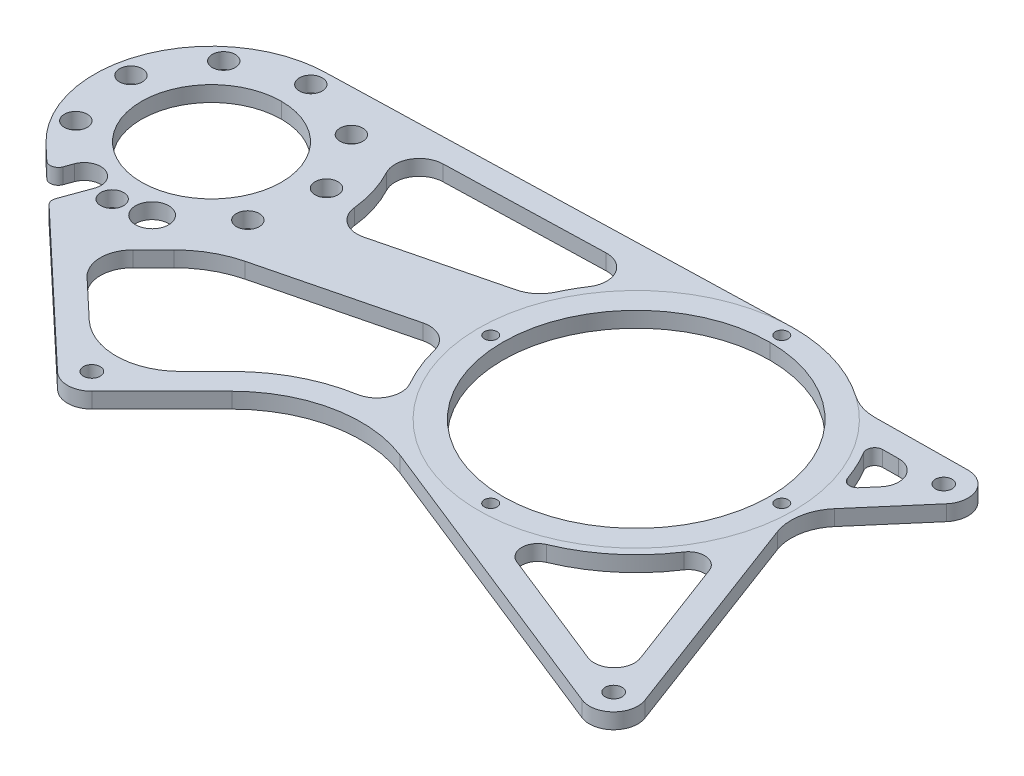
SolidWorks part; units mm, degrees
material "6061-T6 (SS)"
ref_plane "X-Y Datum" through (0, 0, 0) normal (0, 0, 1) x (1, 0, 0)
ref_plane "X-Z Datum" through (0, 0, 0) normal (0, 1, 0) x (1, 0, 0)
ref_plane "Y-Z Datum" through (0, 0, 0) normal (1, 0, 0) x (0, 0, -1)
sketch "Master Sketch " plane through (0, 0, 0) normal (0, 1, 0) x (1, 0, 0)
  line L0 (0, 0) -> (116.84, 0) construction
  line L1 (0, 0) -> (-54.61, 0) construction
  line L2 (116.84, 0) -> (228.6, 0) construction
  line L3 (228.6, 0) -> (228.6, 165.1) construction
  line L4 (123.19, 0) -> (123.19, 116.0018) construction
  line L5 (-54.61, 0) -> (-414.02, 0) construction
  line L6 (-54.61, 0) -> (-54.61, 127) construction
  line L7 (123.19, 168.4528) -> (123.19, 177.9778) construction
  line L8 (123.19, 116.0018) -> (228.6, 165.1) construction
  line L9 (123.19, 116.0018) -> (228.6, 0) construction
  line L10 (0, 0) -> (123.19, 116.0018) construction
  line L11 (0, 0) -> (-54.61, 127) construction
  line L12 (-54.61, 127) -> (123.19, 116.0018) construction
  line L13 (-54.61, 127) -> (228.6, 165.1) construction
  line L14 (0, 0) -> (0, 123.622) construction
  line L15 (-86.1521, 93.553) -> (-6.535, 18.4704)
  line L16 (-54.61, 172.974) -> (123.19, 177.9778)
  line L17 (192.5164, 124.5578) -> (212.8001, 148.1685)
  line L18 (169.599, 163.5141) -> (205.4727, 163.8999)
  line L19 (189.1339, 105.4429) -> (220.4344, 22.1488)
  line L20 (6.7352, 18.6648) -> (34.256, 46.1856)
  line L21 (207.987, 9.9519) -> (89.0101, 57.4446)
  circle A0 centre (0, 0) radius 12.7 construction
  circle A1 centre (228.6, 165.1) radius 12.7 construction
  circle A2 centre (228.6, 0) radius 12.7 construction
  circle A3 centre (-414.02, 0) radius 12.7 construction
  circle A4 centre (123.19, 116.0018) radius 52.451
  circle A5 centre (123.19, 116.0018) radius 57.15 construction
  circle A6 centre (123.19, 116.0018) radius 61.976 construction
  circle A7 centre (-54.61, 127) radius 45.974
  circle A8 centre (-54.61, 127) radius 39 construction
  circle A9 centre (205.5752, 154.3754) radius 3 construction
  circle A10 centre (211.5182, 18.7982) radius 3 construction
  circle A11 centre (0, 25.4) radius 3 construction
  circle A12 centre (0, 25.4) radius 9.525
  circle A13 centre (211.5182, 18.7982) radius 9.525
  circle A14 centre (205.5752, 154.3754) radius 9.525
  circle A15 centre (-67.9488, 90.352) radius 6.5
  circle A16 centre (-41.2712, 90.352) radius 6.5
  arc A17 (56.2619, 120.1418) -> (168.2859, 66.3745) centre (123.19, 116.0018) ccw construction
  arc A18 (123.19, 177.9778) -> (158.5311, 166.9138) centre (123.19, 116.0018) cw
  circle A19 centre (123.19, 116.0018) radius 67.056 construction
  arc A20 (192.5164, 124.5578) -> (189.1339, 105.4429) centre (206.9663, 112.1441) ccw
  arc A21 (169.599, 163.5141) -> (158.5311, 166.9138) centre (169.3942, 182.563) cw
  arc A22 (89.0101, 57.4446) -> (34.256, 46.1856) centre (70.177, 10.2646) ccw
  circle A23 centre (-54.61, 127) radius 25.908 construction
  circle A24 centre (-54.61, 127) radius 27.4955
  circle A25 centre (123.19, 173.1518) radius 2.5 construction
  point P9 (123.19, 0)
  point P23 (-54.61, 166)
  point P27 (-41.2712, 163.648)
  point P28 (-29.5413, 156.8757)
  point P29 (-20.835, 146.5)
  point P30 (-16.2025, 133.7723)
  point P31 (-16.2025, 120.2277)
  point P32 (-20.835, 107.5)
  point P33 (-29.5413, 97.1243)
  point P34 (-41.2712, 90.352)
  point P35 (-54.61, 88)
  point P36 (-67.9488, 90.352)
  point P37 (-79.6787, 97.1243)
  point P38 (-88.385, 107.5)
  point P39 (-93.0175, 120.2277)
  point P40 (-93.0175, 133.7723)
  point P41 (-88.385, 146.5)
  point P42 (-79.6787, 156.8757)
  point P43 (-67.9488, 163.648)
  point P44 (-54.61, 127)
  point P66 (190.246, 116.0018)
  point P74 (185.166, 116.0018)
  point P77 (163.0683, 163.4438)
  point P80 (74.3713, 70.0317)
  dimension "D1" = 105.41
  dimension "D2" = 25.4
  dimension "D8" = 116.0018
  dimension "D11" = 104.902
  dimension "D12" = 114.3
  dimension "D13" = 123.952
  dimension "D14" = 91.948
  dimension "D15" = 78
  dimension "D17" = 6
  dimension "D21" = 19.05
  dimension "D23" = 13
  dimension "D25" = 19.05
  dimension "D26" = 19.05
  dimension "D27" = 50.8
  dimension "D28" = 1.5875
  dimension "D30" = 51.816
  dimension "D31" = 5
  dimension "D3" = 165.1
  dimension "D4" = 171.45
  dimension "D5" = 111.76
  dimension "D6" = 116.84
  dimension "D7" = 54.61
  dimension "D9" = 642.62
  dimension "D10" = 127
  dimension "D18" = 25.4
  dimension "D19" = 25.4
  dimension "D20" = 25.4
  dimension "D22" = 228.6
  dimension "D29" = 45
  dimension "D24" = 5.08
  dimension "D16" = 18
extrude "Boss-Extrude2" add sketch "Master Sketch " along normal mid plane 6.096
hole_wizard "Ø5.0mm Dowel Hole1" positions "Sketch26" profile "Sketch27" hole size "Ø5.0" standard "ANSI Metric" end condition through all
sketch "Sketch26" plane through (0, 3.048, 0) normal (0, 1, 0) x (1, 0, 0)
  point P5 (123.19, 173.1518)
sketch "Sketch27" plane through (123.19, 3.048, -173.1518) normal (1, 0, 0) x (0, 0, 1)
  line L0 (0, 0) -> (0, 6.096)
  line L1 (0, 6.096) -> (2.5, 6.096)
  line L2 (2.5, 6.096) -> (2.5, 0)
  line L5 (2.5, 0) -> (0, 0)
  line L11 (0, -6.35) -> (0, 107.95) construction
  dimension "Thru Hole Dia." = 5
  dimension "Thru Hole Depth" = 6.096
pattern_circular "CirPattern4" count 4 over 360 about axis through (123.19, 0, -116.0018) along (0, 1, 0) of "Ø5.0mm Dowel Hole1"
hole_wizard "M6 Clearance Hole4" positions "Sketch20" profile "Sketch21" hole size "M6" standard "ANSI Metric" end condition through all
sketch "Sketch20" plane through (0, 3.048, 0) normal (0, 1, 0) x (1, 0, 0)
  point P0 (205.5752, 154.3754)
  point P3 (211.5182, 18.7982)
  point P6 (0, 25.4)
  point P9 (205.5752, 154.3754)
sketch "Sketch21" plane through (205.5752, 3.048, -154.3754) normal (1, 0, 0) x (0, 0, 1)
  line L0 (0, 0) -> (0, 6.096)
  line L1 (0, 6.096) -> (3.3, 6.096)
  line L2 (3.3, 6.096) -> (3.3, 0)
  line L5 (3.3, 0) -> (0, 0)
  line L11 (0, -6.35) -> (0, 107.95) construction
  dimension "Thru Hole Dia." = 6.6
  dimension "Thru Hole Depth" = 6.096
hole_wizard "M8 Clearance Hole1" positions "Sketch24" profile "Sketch25" hole size "M8" standard "ANSI Metric" end condition through all
sketch "Sketch24" plane through (0, 3.048, 0) normal (0, 1, 0) x (1, 0, 0)
  point P2 (-54.61, 166)
sketch "Sketch25" plane through (-54.61, 3.048, -166) normal (1, 0, 0) x (0, 0, 1)
  line L0 (0, 0) -> (0, 6.096)
  line L1 (0, 6.096) -> (4.5, 6.096)
  line L2 (4.5, 6.096) -> (4.5, 0)
  line L5 (4.5, 0) -> (0, 0)
  line L11 (0, -6.35) -> (0, 107.95) construction
  dimension "Thru Hole Dia." = 9
  dimension "Thru Hole Depth" = 6.096
pattern_circular "CirPattern3" count 18 over 360 about axis through (-54.61, 3.048, -127) along (0, -1, 0) skipping 1, 3, 5, 7, 8, 10, 11, 13, 15, 17 of "M8 Clearance Hole1"
ref_plane "Plane2" through (-54.61, 0, 0) normal (1, 0, 0) x (0, 0, -1)
ref_plane "Plane1" through (123.19, 0, 0) normal (1, 0, 0) x (0, 0, -1)
split line "Split Line2"
split line "Split Line3"
ref_point "Point2"
ref_point "Point3"
sketch "Sketch28" plane through (0, 3.048, 0) normal (0, 1, 0) x (1, 0, 0)
  circle A0 centre (123.19, 116.0018) radius 61.976 construction
  circle A1 centre (123.19, 116.0018) radius 61.976
split line "Split Line4"
sketch "Topology 1" plane through (0, 3.048, 0) normal (0, 1, 0) x (1, 0, 0)
  line L0 (145.3498, 45.211) -> (198.1607, 24.1302)
  line L1 (206.4589, 32.2614) -> (188.0555, 81.2349)
  line L2 (191.5509, 154.2246) -> (182.6033, 154.1284)
  line L3 (92.5413, 66.2908) -> (211.5182, 18.7982) construction
  line L4 (211.5182, 18.7982) -> (180.2176, 102.0923) construction
  line L5 (190.6048, 136.9496) -> (196.4358, 143.737)
  line L6 (185.2915, 130.7647) -> (205.5752, 154.3754) construction
  line L7 (205.5752, 154.3754) -> (169.7015, 153.9896) construction
  line L8 (6.7352, 18.6648) -> (34.256, 46.1856) construction
  line L9 (119.7044, 177.8797) -> (123.19, 177.9778) construction
  line L10 (119.7044, 177.8797) -> (123.19, 177.9778)
  line L11 (6.7352, 18.6648) -> (34.256, 46.1856)
  line L12 (11.5992, 36.9992) -> (27.5208, 52.9208)
  line L14 (-17.1171, 47.0221) -> (-17.1171, 64.5798)
  line L15 (-6.2723, 77.1436) -> (59.6042, 86.8711)
  line L16 (119.7044, 177.8797) -> (-54.61, 172.974)
  line L17 (-86.1521, 93.553) -> (-6.535, 18.4704)
  line L18 (6.7352, 18.6648) -> (34.256, 46.1856)
  line L19 (89.0101, 57.4446) -> (207.987, 9.9519)
  line L20 (220.4344, 22.1488) -> (189.1339, 105.4429)
  line L21 (192.5164, 124.5578) -> (212.8001, 148.1685)
  line L22 (205.4727, 163.8999) -> (169.599, 163.5141)
  line L23 (119.7044, 177.8797) -> (-54.61, 172.974)
  line L24 (-86.1521, 93.553) -> (-6.535, 18.4704)
  line L26 (89.0101, 57.4446) -> (207.987, 9.9519)
  line L27 (220.4344, 22.1488) -> (189.1339, 105.4429)
  line L28 (192.5164, 124.5578) -> (212.8001, 148.1685)
  line L29 (205.4727, 163.8999) -> (169.599, 163.5141)
  line L30 (73.4651, 167.0496) -> (-14.7002, 164.5684)
  line L31 (-4.4748, 145.7986) -> (62.0635, 147.6712)
  line L32 (-13.1304, 37.7826) -> (-11.934, 36.6543)
  line L33 (119.9724, 168.3585) -> (-54.342, 163.4528) construction
  line L34 (0, 25.4) -> (27.5208, 52.9208) construction
  arc A0 (158.5311, 166.9138) -> (123.19, 177.9778) centre (123.19, 116.0018) ccw construction
  arc A1 (158.5311, 166.9138) -> (123.19, 177.9778) centre (123.19, 116.0018) ccw
  arc A2 (145.5002, 54.1144) -> (179.5195, 82.0197) centre (123.19, 116.0018) ccw
  arc A3 (179.5195, 82.0197) -> (188.0555, 81.2349) centre (183.5974, 79.5596) cw
  arc A4 (119.4901, 181.6837) -> (160.7037, 170.0436) centre (123.19, 116.0018) ccw construction
  arc A5 (145.5002, 54.1144) -> (145.3498, 45.211) centre (147.1154, 49.6341) ccw
  arc A6 (206.4589, 32.2614) -> (198.1607, 24.1302) centre (200.5148, 30.0277) cw
  arc A7 (172.1385, 154.0158) -> (183.7852, 129.0114) centre (123.19, 116.0018) cw
  arc A8 (158.5311, 166.9138) -> (169.599, 163.5141) centre (169.3942, 182.563) ccw
  arc A9 (119.7044, 177.8797) -> (158.5311, 166.9138) centre (123.19, 116.0018) ccw
  arc A10 (-54.61, 172.974) -> (-86.1521, 93.553) centre (-54.61, 127) ccw
  arc A11 (-6.535, 18.4704) -> (6.7352, 18.6648) centre (0, 25.4) ccw
  arc A12 (89.0101, 57.4446) -> (34.256, 46.1856) centre (70.177, 10.2646) ccw
  arc A13 (207.987, 9.9519) -> (220.4344, 22.1488) centre (211.5182, 18.7982) ccw
  arc A14 (192.5164, 124.5578) -> (189.1339, 105.4429) centre (206.9663, 112.1441) ccw
  arc A15 (212.8001, 148.1685) -> (205.4727, 163.8999) centre (205.5752, 154.3754) ccw
  arc A16 (158.5311, 166.9138) -> (169.599, 163.5141) centre (169.3942, 182.563) ccw
  arc A17 (119.7044, 177.8797) -> (158.5311, 166.9138) centre (123.19, 116.0018) ccw
  arc A18 (-54.61, 172.974) -> (-86.1521, 93.553) centre (-54.61, 127) ccw
  arc A19 (-6.535, 18.4704) -> (6.7352, 18.6648) centre (0, 25.4) ccw
  arc A21 (207.987, 9.9519) -> (220.4344, 22.1488) centre (211.5182, 18.7982) ccw
  arc A22 (192.5164, 124.5578) -> (189.1339, 105.4429) centre (206.9663, 112.1441) ccw
  arc A23 (212.8001, 148.1685) -> (205.4727, 163.8999) centre (205.5752, 154.3754) ccw
  arc A24 (179.9004, 149.3443) -> (185.2036, 137.9589) centre (123.19, 116.0018) cw
  arc A25 (175.1477, 156.3527) -> (187.5103, 129.8112) centre (123.19, 116.0018) cw construction
  arc A26 (190.6048, 136.9496) -> (185.2036, 137.9589) centre (188.1965, 139.0186) cw
  arc A27 (182.6033, 154.1284) -> (179.9004, 149.3443) centre (182.6374, 150.9535) ccw
  arc A28 (196.4358, 143.737) -> (191.5509, 154.2246) centre (191.6192, 147.875) ccw
  arc A29 (89.0101, 57.4446) -> (34.256, 46.1856) centre (70.177, 10.2646) ccw construction
  arc A30 (89.0101, 57.4446) -> (34.256, 46.1856) centre (70.177, 10.2646) ccw
  arc A31 (63.8869, 70.2607) -> (27.5208, 52.9208) centre (70.177, 10.2646) ccw
  arc A32 (7.5766, 36.6135) -> (-7.9019, 36.3867) centre (0, 25.4) ccw
  arc A33 (67.8443, 88.1113) -> (82.4046, 69.3373) centre (123.19, 116.0018) ccw
  arc A34 (65.8116, 83.8223) -> (68.3344, 79.6884) centre (123.19, 116.0018) ccw
  arc A35 (64.4419, 86.3967) -> (79.8973, 66.4686) centre (123.19, 116.0018) ccw construction
  arc A36 (-10.3254, 149.2911) -> (-17.0182, 159.3246) centre (-54.61, 127) ccw
  arc A37 (70.0507, 147.896) -> (88.6754, 167.4777) centre (123.19, 116.0018) cw
  arc A38 (67.2815, 150.6721) -> (75.8397, 161.6717) centre (123.19, 116.0018) cw
  arc A39 (66.7839, 149.8567) -> (86.5536, 170.6422) centre (123.19, 116.0018) cw construction
  arc A40 (-17.0182, 159.3246) -> (-14.7002, 164.5684) centre (-14.6109, 161.3947) cw
  arc A41 (92.5413, 66.2908) -> (27.5208, 52.9208) centre (70.177, 10.2646) ccw construction
  arc A42 (-10.3254, 149.2911) -> (-4.4748, 145.7986) centre (-4.6534, 152.1461) ccw
  arc A43 (67.2815, 150.6721) -> (62.0635, 147.6712) centre (61.8849, 154.0187) cw
  arc A44 (75.8397, 161.6717) -> (73.4651, 167.0496) centre (73.5544, 163.8759) ccw
  arc A45 (-6.2723, 77.1436) -> (-17.1171, 64.5798) centre (-4.4171, 64.5798) ccw
  arc A46 (-17.1171, 47.0221) -> (-13.1304, 37.7826) centre (-4.4171, 47.0221) ccw
  arc A47 (7.5766, 36.6135) -> (11.5992, 36.9992) centre (9.3541, 39.2442) ccw
  arc A48 (-7.9019, 36.3867) -> (-11.934, 36.6543) centre (-9.7557, 38.9642) cw
  arc A49 (65.8116, 83.8223) -> (59.6042, 86.8711) centre (60.4947, 80.8405) ccw
  arc A50 (68.3344, 79.6884) -> (63.8869, 70.2607) centre (63.2512, 76.3235) cw
  point P69 (-79.6171, 100.4826)
  point P105 (-17.1171, 75.5422)
  point P108 (-17.1171, 41.5422)
  dimension "D4" = 4.7625
  dimension "D5" = 6.35
  dimension "D8" = 3.175
  dimension "D9" = 6.35
  dimension "D11" = 3.175
  dimension "D17" = 6.35
  dimension "D18" = 6.35
  dimension "D19" = 3.175
  dimension "D20" = 12.7
  dimension "D21" = 12.7
  dimension "D22" = 3.175
  dimension "D23" = 6.096
  dimension "D24" = 49.5784
  dimension "D25" = 13.5331
  dimension "D14" = 19.05
  dimension "D15" = 34
  dimension "D1" = 0
  dimension "D2" = 9.525
  dimension "D3" = 3.81
  dimension "D6" = 9.525
  dimension "D7" = 3.81
  dimension "D10" = 9.525
  dimension "D12" = 3.81
  dimension "D13" = 9.525
  dimension "D16" = 3.81
sketch "Topology 3" plane through (0, 3.048, 0) normal (0, 1, 0) x (1, 0, 0)
  line L0 (148.2326, 44.0603) -> (194.8213, 25.4632)
  line L1 (205.1941, 35.6272) -> (188.9001, 78.9873)
  line L2 (188.0448, 154.1869) -> (181.8702, 154.1205)
  line L3 (190.1271, 136.3935) -> (194.151, 141.0774)
  line L4 (185.2915, 130.7647) -> (205.5752, 154.3754) construction
  line L5 (17.4418, 42.8418) -> (27.5208, 52.9208)
  line L6 (-33.0328, 56.5514) -> (-17.9453, 42.3233)
  line L7 (119.7044, 177.8797) -> (-54.61, 172.974)
  line L8 (-86.1521, 93.553) -> (-6.535, 18.4704)
  line L9 (6.7352, 18.6648) -> (34.256, 46.1856)
  line L10 (89.0101, 57.4446) -> (207.987, 9.9519)
  line L11 (220.4344, 22.1488) -> (189.1339, 105.4429)
  line L12 (192.5164, 124.5578) -> (212.8001, 148.1685)
  line L13 (205.4727, 163.8999) -> (169.599, 163.5141)
  line L14 (119.7044, 177.8797) -> (-54.61, 172.974)
  line L15 (-86.1521, 93.553) -> (-6.535, 18.4704)
  line L16 (6.7352, 18.6648) -> (34.256, 46.1856)
  line L17 (89.0101, 57.4446) -> (207.987, 9.9519)
  line L18 (220.4344, 22.1488) -> (189.1339, 105.4429)
  line L19 (192.5164, 124.5578) -> (212.8001, 148.1685)
  line L20 (205.4727, 163.8999) -> (169.599, 163.5141)
  line L22 (-7.4578, 92.9346) -> (48.4864, 106.9206)
  line L23 (60.6168, 166.688) -> (-1.6638, 164.9353)
  line L24 (7.6514, 124.4645) -> (55.6594, 136.4665)
  line L25 (-33.2997, 74.7712) -> (-25.158, 82.9129)
  line L26 (119.9724, 168.3585) -> (-54.342, 163.4528) construction
  line L27 (-79.6171, 100.4826) -> (0, 25.4) construction
  line L28 (0, 25.4) -> (27.5208, 52.9208) construction
  line L29 (92.5413, 66.2908) -> (211.5182, 18.7982) construction
  line L30 (211.5182, 18.7982) -> (180.2176, 102.0923) construction
  line L32 (205.5752, 154.3754) -> (169.7015, 153.9896) construction
  arc A0 (123.19, 54.0258) -> (182.1581, 96.9285) centre (123.19, 116.0018) ccw
  arc A1 (148.1536, 55.8231) -> (177.6482, 80.2392) centre (123.19, 116.0018) ccw
  arc A2 (172.1385, 154.0158) -> (183.7852, 129.0114) centre (123.19, 116.0018) cw
  arc A3 (179.1759, 149.3219) -> (184.7202, 137.4188) centre (123.19, 116.0018) cw
  arc A4 (59.8962, 69.7071) -> (27.5208, 52.9208) centre (70.177, 10.2646) ccw
  arc A7 (61.4889, 110.1712) -> (82.4046, 69.3373) centre (123.19, 116.0018) ccw
  arc A8 (158.5311, 166.9138) -> (169.599, 163.5141) centre (169.3942, 182.563) ccw
  arc A9 (119.7044, 177.8797) -> (158.5311, 166.9138) centre (123.19, 116.0018) ccw
  arc A10 (-54.61, 172.974) -> (-86.1521, 93.553) centre (-54.61, 127) ccw
  arc A11 (-6.535, 18.4704) -> (6.7352, 18.6648) centre (0, 25.4) ccw
  arc A12 (89.0101, 57.4446) -> (34.256, 46.1856) centre (70.177, 10.2646) ccw
  arc A13 (207.987, 9.9519) -> (220.4344, 22.1488) centre (211.5182, 18.7982) ccw
  arc A14 (192.5164, 124.5578) -> (189.1339, 105.4429) centre (206.9663, 112.1441) ccw
  arc A15 (212.8001, 148.1685) -> (205.4727, 163.8999) centre (205.5752, 154.3754) ccw
  arc A16 (158.5311, 166.9138) -> (169.599, 163.5141) centre (169.3942, 182.563) ccw
  arc A17 (119.7044, 177.8797) -> (158.5311, 166.9138) centre (123.19, 116.0018) ccw
  arc A18 (-54.61, 172.974) -> (-86.1521, 93.553) centre (-54.61, 127) ccw
  arc A19 (-6.535, 18.4704) -> (6.7352, 18.6648) centre (0, 25.4) ccw
  arc A20 (89.0101, 57.4446) -> (34.256, 46.1856) centre (70.177, 10.2646) ccw
  arc A21 (207.987, 9.9519) -> (220.4344, 22.1488) centre (211.5182, 18.7982) ccw
  arc A22 (192.5164, 124.5578) -> (189.1339, 105.4429) centre (206.9663, 112.1441) ccw
  arc A23 (212.8001, 148.1685) -> (205.4727, 163.8999) centre (205.5752, 154.3754) ccw
  arc A24 (60.0304, 100.017) -> (66.5532, 83.8005) centre (123.19, 116.0018) ccw
  arc A25 (63.439, 132.459) -> (88.6754, 167.4777) centre (123.19, 116.0018) cw
  arc A26 (64.0981, 143.4389) -> (68.8318, 151.9162) centre (123.19, 116.0018) cw
  arc A27 (-4.1248, 132.6464) -> (-9.7981, 150.9276) centre (-54.61, 127) ccw
  arc A28 (92.5413, 66.2908) -> (27.5208, 52.9208) centre (70.177, 10.2646) ccw construction
  arc A29 (58.328, 109.8725) -> (80.3152, 66.9467) centre (123.19, 116.0018) ccw construction
  arc A30 (60.378, 133.3021) -> (86.9072, 170.1148) centre (123.19, 116.0018) cw construction
  arc A31 (123.19, 50.8508) -> (185.179, 95.9514) centre (123.19, 116.0018) ccw construction
  arc A32 (174.6461, 155.9633) -> (186.8894, 129.6779) centre (123.19, 116.0018) cw construction
  arc A33 (205.1941, 35.6272) -> (194.8213, 25.4632) centre (197.7639, 32.8351) cw
  arc A34 (188.9001, 78.9873) -> (177.6482, 80.2392) centre (182.956, 76.7536) ccw
  arc A35 (148.1536, 55.8231) -> (148.2326, 44.0603) centre (150.5867, 49.9578) ccw
  arc A36 (184.7202, 137.4188) -> (190.1271, 136.3935) centre (187.7188, 138.4625) ccw
  arc A37 (181.8702, 154.1205) -> (179.1759, 149.3219) centre (181.9043, 150.9457) ccw
  arc A38 (194.151, 141.0774) -> (188.0448, 154.1869) centre (188.1302, 146.2498) ccw
  arc A42 (48.4864, 106.9206) -> (60.0304, 100.017) centre (50.7965, 97.68) cw
  arc A43 (59.8962, 69.7071) -> (66.5532, 83.8005) centre (58.2729, 79.0927) ccw
  arc A46 (-1.6638, 164.9353) -> (-9.7981, 150.9276) centre (-1.3958, 155.4141) ccw
  arc A47 (7.6514, 124.4645) -> (-4.1248, 132.6464) centre (5.3412, 133.7051) cw
  arc A48 (55.6594, 136.4665) -> (64.0981, 143.4389) centre (52.5792, 148.7873) ccw
  arc A49 (68.8318, 151.9162) -> (60.6168, 166.688) centre (60.8847, 157.1668) ccw
  arc A50 (-33.2997, 74.7712) -> (-33.0328, 56.5514) centre (-24.3195, 65.7909) ccw
  arc A51 (-6.535, 18.4704) -> (6.7352, 18.6648) centre (0, 25.4) ccw
  arc A55 (-7.4578, 92.9346) -> (-25.158, 82.9129) centre (1.7828, 55.9721) ccw
  arc A59 (17.4418, 42.8418) -> (-17.9453, 42.3233) centre (-0.5187, 60.8023) cw
  point P97 (6.7352, 32.1352)
  dimension "D11" = 7.9375
  dimension "D12" = 6.35
  dimension "D13" = 12.7
  dimension "D14" = 7.9375
  dimension "D15" = 25.4
  dimension "D16" = 38.1
  dimension "D17" = 9.525
  dimension "D21" = 9.525
  dimension "D22" = 9.525
  dimension "D23" = 12.7
  dimension "D24" = 9.525
  dimension "D25" = 50.8
  dimension "D20" = 26.924
  dimension "D26" = 52
  dimension "D1" = 0
  dimension "D2" = 9.525
  dimension "D3" = 3.175
  dimension "D4" = 9.525
  dimension "D5" = 3.175
  dimension "D6" = 9.525
  dimension "D7" = 9.525
  dimension "D8" = 3.175
  dimension "D9" = 9.525
  dimension "D10" = 3.175
extrude "Cut-Extrude1" [suppressed] cut sketch "Topology 1" against normal through all contours A38 A44 L30 A40 A36 A42 L31 A43 | A50 A34 A49 L15 A45 L14 A46 L32 A48 A32 A47 L12 A31 | A6 L1 A3 A2 A5 L0 | L5 A28 L2 A27 A24 A26
extrude "Cut-Extrude2" cut sketch "Topology 3" against normal through all
sketch "Sketch29" plane through (0, 3.048, 0) normal (0, 1, 0) x (1, 0, 0)
  line L0 (-86.1521, 93.553) -> (-6.535, 18.4704)
  line L1 (-54.61, 166) -> (-54.61, 88) construction
  line L2 (-58.4616, 116.4177) -> (-77.4359, 64.2863) construction
  line L3 (-74.0568, 92.5751) -> (-76.8826, 84.8114)
  line L4 (-86.1521, 93.553) -> (-6.535, 18.4704) construction
  line L5 (-61.8408, 88.1289) -> (-66.5834, 75.0987)
  circle A0 centre (-67.9488, 90.352) radius 6.5 construction
  circle A1 centre (-67.9488, 90.352) radius 6.5
  point P6 (-54.61, 127)
  point P9 (-67.9488, 90.352)
  point P10 (-67.9488, 90.352)
  dimension "D1" = 20
extrude "Cut-Extrude4" cut sketch "Sketch29" against normal through all
fillet "Fillet1" radius 3.175 2 edges at (-66.5834, 0, -75.0987) (-76.8826, 0, -84.8114)
